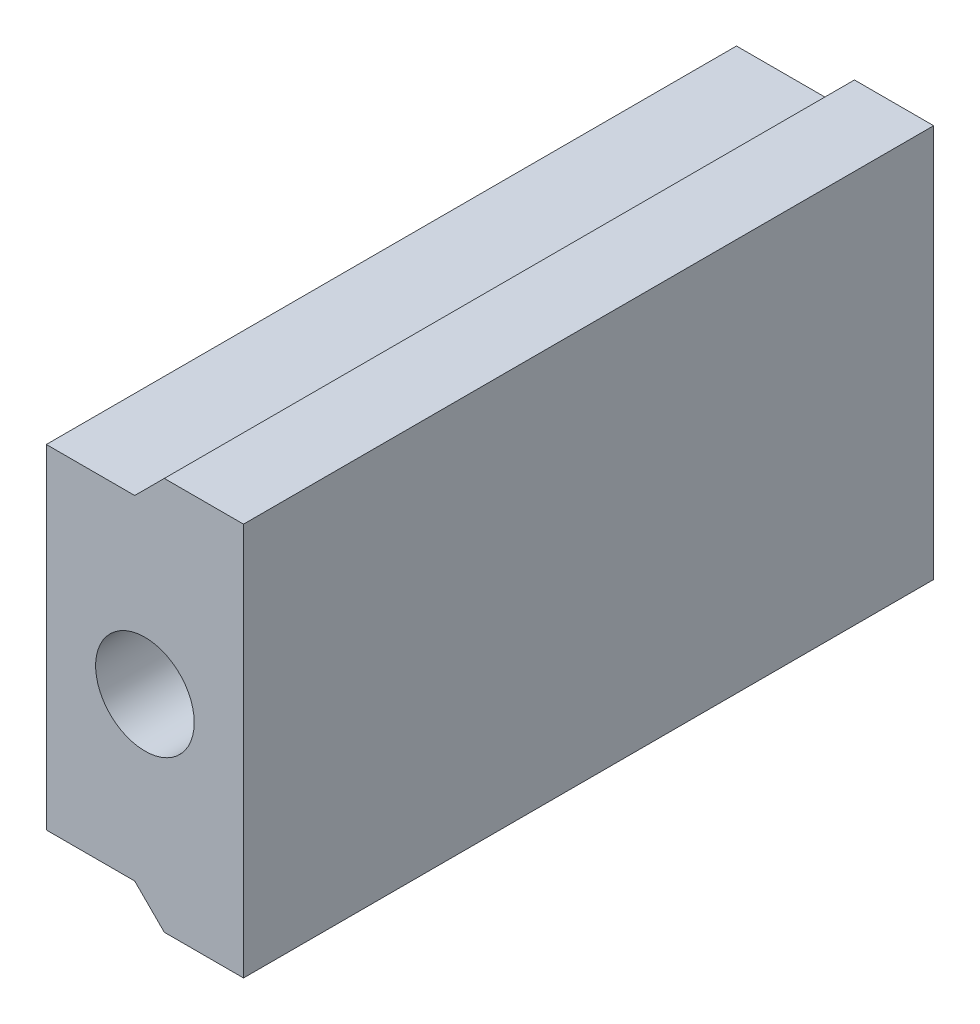
SolidWorks part; units mm, degrees
ref_plane "前视基准面" through (0, 0, 0) normal (0, 0, 1) x (1, 0, 0)
ref_plane "上视基准面" through (0, 0, 0) normal (0, 1, 0) x (1, 0, 0)
ref_plane "右视基准面" through (0, 0, 0) normal (1, 0, 0) x (0, 0, -1)
other "Configuration Table"
sketch "草图1" plane through (0, 0, 0) normal (0, 0, 1) x (1, 0, 0)
  line L0 (0, 0) -> (0, 50000) construction
  line L1 (0, 0) -> (50000, 0) construction
  line L3 (-10, 19.9329) -> (10, 19.9329)
  line L4 (-10, 19.9329) -> (-10, -19.9329)
  line L5 (-10, -19.9329) -> (10, -19.9329)
  line L6 (10, 19.9329) -> (10, -19.9329)
extrude "凸台-拉伸1" add sketch "草图1" along normal blind 70
sketch "草图2" plane through (0, 0, 70) normal (0, 0, 1) x (1, 0, 0)
  line L0 (0, 0) -> (0, 50000) construction
  line L1 (0, 0) -> (50000, 0) construction
  line L2 (10, -19.9329) -> (1.9647, -19.9329)
  line L3 (-10, -19.9329) -> (10, -19.9329) construction
  line L4 (1.9647, -19.9329) -> (-1.0353, -16.9329)
  line L5 (1.9647, -19.9329) -> (1.9647, -16.9329)
  line L7 (1.9647, -16.9329) -> (-1.0353, -16.9329)
  line L8 (-1.0353, -16.9329) -> (-10, -16.9329)
  line L9 (-10, 19.9329) -> (-10, -19.9329) construction
  line L10 (1.9647, -19.9329) -> (-10, -19.9329)
  line L11 (-10, -19.9329) -> (-10, -16.9329)
  line L12 (-10, 19.9329) -> (-10, 16.9329)
  line L13 (1.9647, 19.9329) -> (-10, 19.9329)
  line L14 (-1.0353, 16.9329) -> (-10, 16.9329)
  line L15 (1.9647, 19.9329) -> (-1.0353, 16.9329)
  line M9 (-10, 19.9329) -> (-10, -19.9329)
  line M10 (-10, -19.9329) -> (10, -19.9329)
  line M12 (10, 19.9329) -> (-10, 19.9329)
  dimension "D1" = 45
extrude "切除-拉伸1" cut sketch "草图2" against normal blind 70 contours L4 L8 M9 M10 | L15 L14 M12 M9
sketch "草图3" plane through (0, 0, 70) normal (0, 0, 1) x (1, 0, 0)
  line L0 (0, 0) -> (0, 50000) construction
  line L1 (0, 0) -> (50000, 0) construction
  circle A0 centre (0, 0) radius 5
extrude "切除-拉伸2" cut sketch "草图3" against normal through all
